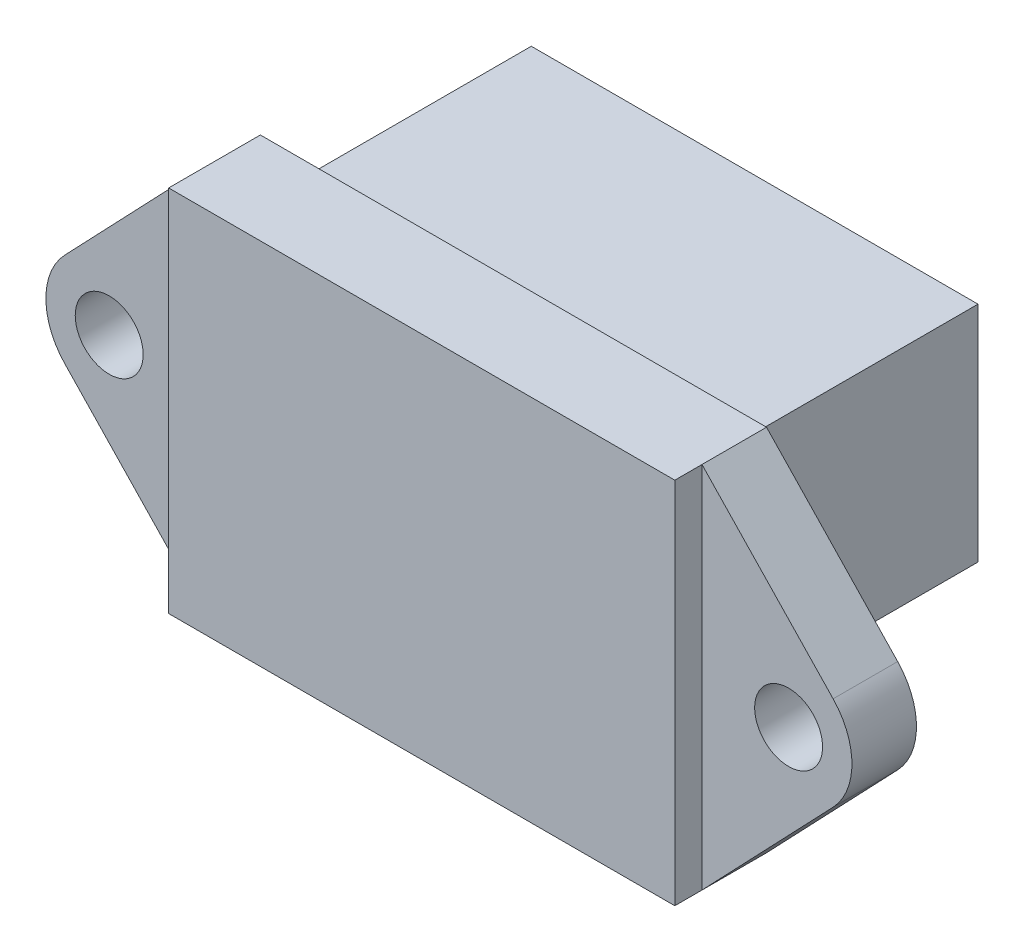
SolidWorks part; units mm, degrees
ref_plane "Front Plane" through (0, 0, 0) normal (0, 0, 1) x (1, 0, 0)
ref_plane "Top Plane" through (0, 0, 0) normal (0, 1, 0) x (1, 0, 0)
ref_plane "Right Plane" through (0, 0, 0) normal (1, 0, 0) x (0, 0, -1)
sketch "Sketch1" plane through (0, 0, 0) normal (0, 0, 1) x (1, 0, 0)
  line L1 (-14.9, -10.85) -> (14.9, -10.85)
  line L2 (-14.9, -10.85) -> (-14.9, 10.85)
  line L3 (-14.9, 10.85) -> (14.9, 10.85)
  line L4 (14.9, -10.85) -> (14.9, 10.85)
  line L5 (-14.9, -10.85) -> (14.9, 10.85) construction
  line L6 (-14.9, 10.85) -> (14.9, -10.85) construction
  point P0 (0, 0)
  dimension "D1" = 29.8
  dimension "D2" = 21.7
extrude "Boss-Extrude1" add sketch "Sketch1" along normal blind 5.4
sketch "Sketch2" plane through (0, 0, 0) normal (0, 0, 1) x (1, 0, 0)
  line L0 (14.9, 10.85) -> (14.9, -10.85)
  line L1 (14.9, -10.85) -> (25.2575, 0)
  line L2 (25.2575, 0) -> (14.9, 10.85)
  line L3 (-14.9, 10.85) -> (-14.9, -10.85)
  line L4 (-14.9, -10.85) -> (-25.2575, 0)
  line L5 (-25.2575, 0) -> (-14.9, 10.85)
  line L6 (-18, 0) -> (18, 0) construction
  circle A0 centre (-20, 0) radius 2
  circle A1 centre (20, 0) radius 2
  dimension "D1" = 4
  dimension "D2" = 15
  dimension "D3" = 36
extrude "Boss-Extrude2" add sketch "Sketch2" along normal blind 3.8
fillet "Fillet1" radius 4 2 edges at (-25.2575, 0, 1.9) (25.2575, 0, 1.9)
sketch "Sketch3" plane through (0, 0, 0) normal (0, 0, -1) x (-1, 0, 0)
  line L0 (-13.15, 9.15) -> (13.15, 9.15)
  line L1 (13.15, 9.15) -> (13.15, -4)
  line L2 (13.15, -4) -> (8, -9.15)
  line L3 (8, -9.15) -> (-8, -9.15)
  line L4 (-8, -9.15) -> (-13.15, -4)
  line L5 (-13.15, -4) -> (-13.15, 9.15)
  line L6 (-14.9, 10.85) -> (14.9, 10.85) construction
  point P2 (0, -9.15)
  point P7 (0, 9.15)
  dimension "D1" = 18.3
  dimension "D2" = 26.3
  dimension "D3" = 1.7
  dimension "D4" = 16
extrude "Boss-Extrude3" add sketch "Sketch3" along normal blind 14.2
